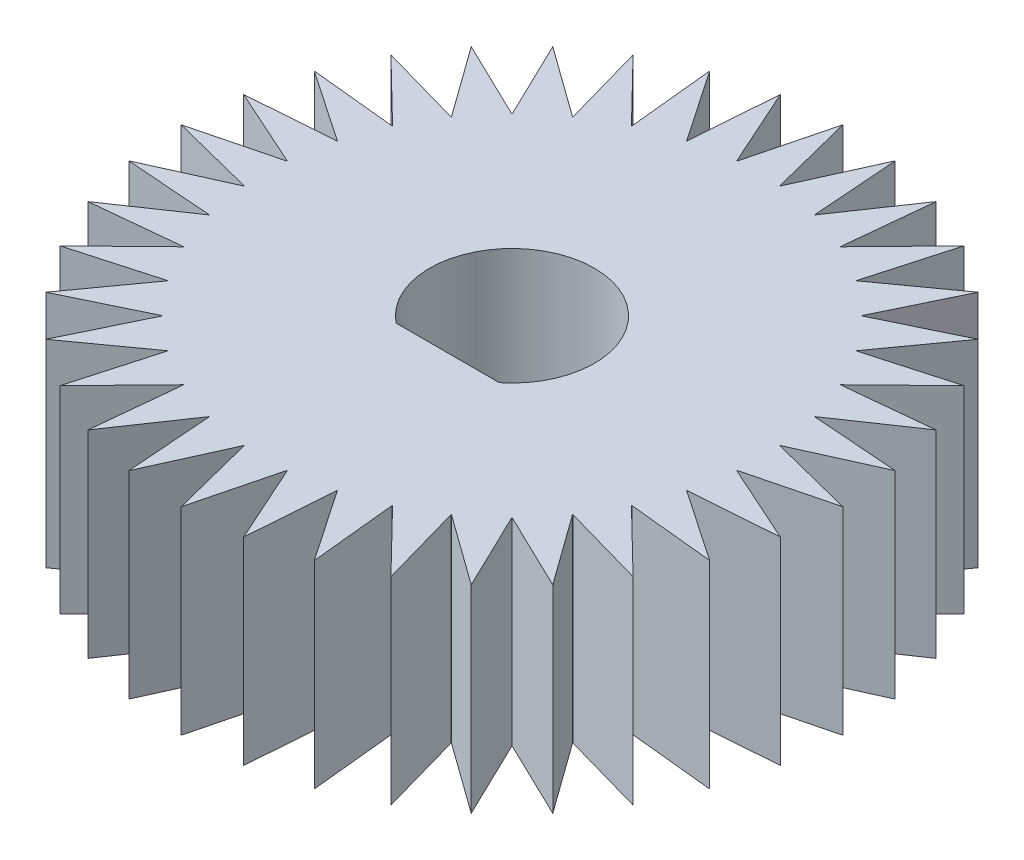
SolidWorks part; units mm, degrees
ref_plane "Спереди" through (0, 0, 0) normal (0, 0, 1) x (1, 0, 0)
ref_plane "Сверху" through (0, 0, 0) normal (0, 1, 0) x (1, 0, 0)
ref_plane "Справа" through (0, 0, 0) normal (1, 0, 0) x (0, 0, -1)
sketch "Эскиз1" plane through (0, 0, 0) normal (0, 1, 0) x (1, 0, 0)
  line L2 (-0.6494, 7.4718) -> (0, 10.03)
  line L222 (-1.5644, -1.95) -> (1.5644, -1.95)
  line L225 (0.6494, 7.4718) -> (0, 10.03)
  line L228 (1.937, 7.2456) -> (1.7417, 9.8776)
  line L229 (0.6579, 7.4711) -> (1.7417, 9.8776)
  line L230 (3.1657, 6.7991) -> (3.4305, 9.4251)
  line L231 (1.9453, 7.2433) -> (3.4305, 9.4251)
  line L232 (4.2983, 6.1461) -> (5.015, 8.6862)
  line L233 (3.1735, 6.7955) -> (5.015, 8.6862)
  line L234 (5.3003, 5.3063) -> (6.4472, 7.6834)
  line L235 (4.3053, 6.1412) -> (6.4472, 7.6834)
  line L236 (6.1412, 4.3053) -> (7.6834, 6.4472)
  line L237 (5.3063, 5.3003) -> (7.6834, 6.4472)
  line L238 (6.7955, 3.1735) -> (8.6862, 5.015)
  line L239 (6.1461, 4.2983) -> (8.6862, 5.015)
  line L240 (7.2433, 1.9453) -> (9.4251, 3.4305)
  line L241 (6.7991, 3.1657) -> (9.4251, 3.4305)
  line L242 (7.4711, 0.6579) -> (9.8776, 1.7417)
  line L243 (7.2456, 1.937) -> (9.8776, 1.7417)
  line L244 (7.4718, -0.6494) -> (10.03, 0)
  line L245 (7.4718, 0.6494) -> (10.03, 0)
  line L246 (7.2456, -1.937) -> (9.8776, -1.7417)
  line L247 (7.4711, -0.6579) -> (9.8776, -1.7417)
  line L248 (6.7991, -3.1657) -> (9.4251, -3.4305)
  line L249 (7.2433, -1.9453) -> (9.4251, -3.4305)
  line L250 (6.1461, -4.2983) -> (8.6862, -5.015)
  line L251 (6.7955, -3.1735) -> (8.6862, -5.015)
  line L252 (5.3063, -5.3003) -> (7.6834, -6.4472)
  line L253 (6.1412, -4.3053) -> (7.6834, -6.4472)
  line L254 (4.3053, -6.1412) -> (6.4472, -7.6834)
  line L255 (5.3003, -5.3063) -> (6.4472, -7.6834)
  line L256 (3.1735, -6.7955) -> (5.015, -8.6862)
  line L257 (4.2983, -6.1461) -> (5.015, -8.6862)
  line L258 (1.9453, -7.2433) -> (3.4305, -9.4251)
  line L259 (3.1657, -6.7991) -> (3.4305, -9.4251)
  line L260 (0.6579, -7.4711) -> (1.7417, -9.8776)
  line L261 (1.937, -7.2456) -> (1.7417, -9.8776)
  line L262 (-0.6494, -7.4718) -> (0, -10.03)
  line L263 (0.6494, -7.4718) -> (0, -10.03)
  line L264 (-1.937, -7.2456) -> (-1.7417, -9.8776)
  line L265 (-0.6579, -7.4711) -> (-1.7417, -9.8776)
  line L266 (-3.1657, -6.7991) -> (-3.4305, -9.4251)
  line L267 (-1.9453, -7.2433) -> (-3.4305, -9.4251)
  line L268 (-4.2983, -6.1461) -> (-5.015, -8.6862)
  line L269 (-3.1735, -6.7955) -> (-5.015, -8.6862)
  line L270 (-5.3003, -5.3063) -> (-6.4472, -7.6834)
  line L271 (-4.3053, -6.1412) -> (-6.4472, -7.6834)
  line L272 (-6.1412, -4.3053) -> (-7.6834, -6.4472)
  line L273 (-5.3063, -5.3003) -> (-7.6834, -6.4472)
  line L274 (-6.7955, -3.1735) -> (-8.6862, -5.015)
  line L275 (-6.1461, -4.2983) -> (-8.6862, -5.015)
  line L276 (-7.2433, -1.9453) -> (-9.4251, -3.4305)
  line L277 (-6.7991, -3.1657) -> (-9.4251, -3.4305)
  line L278 (-7.4711, -0.6579) -> (-9.8776, -1.7417)
  line L279 (-7.2456, -1.937) -> (-9.8776, -1.7417)
  line L280 (-7.4718, 0.6494) -> (-10.03, 0)
  line L281 (-7.4718, -0.6494) -> (-10.03, 0)
  line L282 (-7.2456, 1.937) -> (-9.8776, 1.7417)
  line L283 (-7.4711, 0.6579) -> (-9.8776, 1.7417)
  line L284 (-6.7991, 3.1657) -> (-9.4251, 3.4305)
  line L285 (-7.2433, 1.9453) -> (-9.4251, 3.4305)
  line L286 (-6.1461, 4.2983) -> (-8.6862, 5.015)
  line L287 (-6.7955, 3.1735) -> (-8.6862, 5.015)
  line L288 (-5.3063, 5.3003) -> (-7.6834, 6.4472)
  line L289 (-6.1412, 4.3053) -> (-7.6834, 6.4472)
  line L290 (-4.3053, 6.1412) -> (-6.4472, 7.6834)
  line L291 (-5.3003, 5.3063) -> (-6.4472, 7.6834)
  line L292 (-3.1735, 6.7955) -> (-5.015, 8.6862)
  line L293 (-4.2983, 6.1461) -> (-5.015, 8.6862)
  line L294 (-1.9453, 7.2433) -> (-3.4305, 9.4251)
  line L295 (-3.1657, 6.7991) -> (-3.4305, 9.4251)
  line L296 (-0.6579, 7.4711) -> (-1.7417, 9.8776)
  line L297 (-1.937, 7.2456) -> (-1.7417, 9.8776)
  arc A6 (-1.5644, -1.95) -> (1.5644, -1.95) centre (0, 0) cw
  circle A7 centre (0, 0) radius 7.5
  point P80 (0, 0)
  point P117 (0, 0)
  point P158 (0, 0)
  point P224 (0, 0)
extrude "Бобышка-Вытянуть2" add sketch "Эскиз1" along normal blind 6
